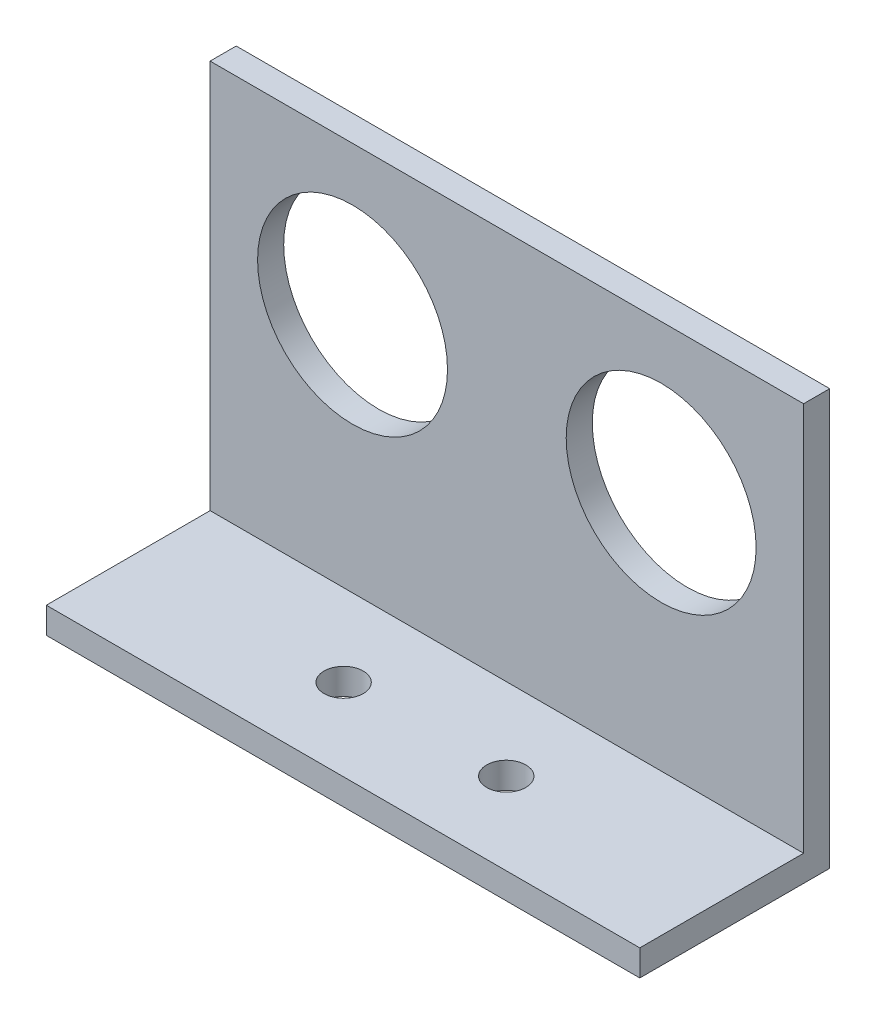
SolidWorks part; units mm, degrees
ref_plane "前视基准面" through (0, 0, 0) normal (0, 0, 1) x (1, 0, 0)
ref_plane "上视基准面" through (0, 0, 0) normal (0, 1, 0) x (1, 0, 0)
ref_plane "右视基准面" through (0, 0, 0) normal (1, 0, 0) x (0, 0, -1)
sketch "草图1" plane through (0, 0, 0) normal (0, 0, 1) x (1, 0, 0)
  line L0 (0, 0) -> (50, 0)
  line L1 (50, 0) -> (50, 35)
  line L2 (50, 35) -> (0, 35)
  line L3 (0, 35) -> (0, 0)
extrude "凸台-拉伸1" add sketch "草图1" along normal blind 2.2
sketch "草图2" plane through (0, 0, 2.2) normal (0, 0, 1) x (1, 0, 0)
  circle A0 centre (12, 22.5) radius 8
  circle A1 centre (38, 22.5) radius 8
extrude "切除-拉伸1" cut sketch "草图2" against normal blind 2.2
sketch "草图3" plane through (0, 0, 2.2) normal (0, 0, 1) x (1, 0, 0)
  line L0 (0, 0) -> (0, 2.2)
  line L1 (0, 35) -> (0, 0) construction
  line L2 (0, 2.2) -> (50, 2.2)
  line L3 (50, 0) -> (50, 35) construction
  line L4 (50, 2.2) -> (50, 0)
  line L5 (50, 0) -> (0, 0)
extrude "凸台-拉伸2" add sketch "草图3" along normal blind 13.8
sketch "草图4" plane through (0, 2.2, 0) normal (0, 1, 0) x (1, 0, 0)
  line L3 (25, -9.1) -> (25, -16)
  line L4 (50, -16) -> (0, -16) construction
  circle A0 centre (18.15, -9.1) radius 1.65
  circle A1 centre (31.85, -9.1) radius 1.65
extrude "切除-拉伸2" cut sketch "草图4" against normal blind 13.8 contours A0 | A1
